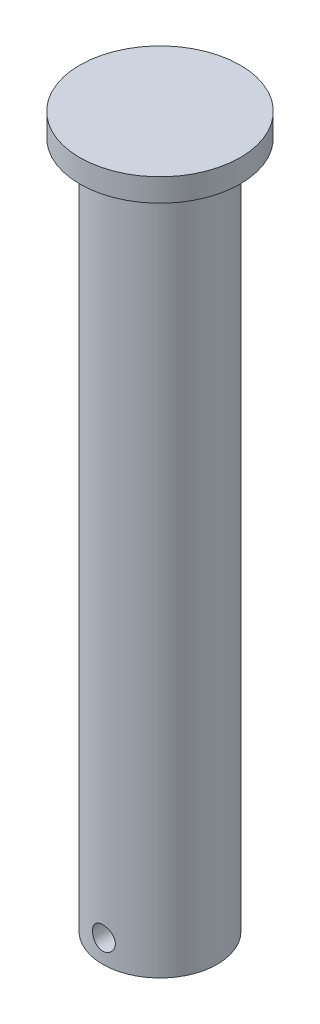
SolidWorks part; units mm, degrees
ref_plane "Alzado" through (0, 0, 0) normal (0, 0, 1) x (1, 0, 0)
ref_plane "Planta" through (0, 0, 0) normal (0, 1, 0) x (1, 0, 0)
ref_plane "Vista lateral" through (0, 0, 0) normal (1, 0, 0) x (0, 0, -1)
sketch "Croquis2" plane through (0, 0, 0) normal (0, 1, 0) x (1, 0, 0)
  circle A0 centre (0, 0) radius 5
  dimension "D1" = 10
extrude "Saliente-Extruir1" add sketch "Croquis2" along normal blind 60
sketch "Croquis3" plane through (0, 60, 0) normal (0, 1, 0) x (1, 0, 0)
  circle A0 centre (0, 0) radius 7
  dimension "D1" = 14
extrude "Saliente-Extruir2" add sketch "Croquis3" along normal blind 2
sketch "Croquis4" plane through (0, 0, 0) normal (0, 0, 1) x (1, 0, 0)
  line L0 (0, 0) -> (0, 2) construction
  circle A0 centre (0, 2) radius 1
  dimension "D2" = 2
  dimension "D1" = 2
extrude "Cortar-Extruir1" cut sketch "Croquis4" against normal up to body and the other way through all separate body
